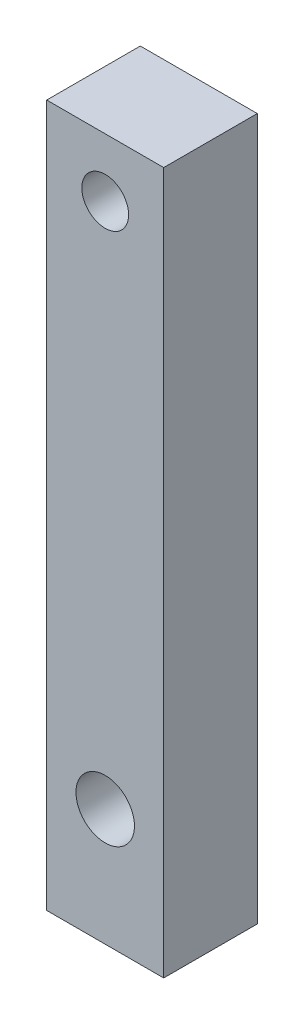
SolidWorks part; units mm, degrees
ref_plane "前视基准面" through (0, 0, 0) normal (0, 0, 1) x (1, 0, 0)
ref_plane "上视基准面" through (0, 0, 0) normal (0, 1, 0) x (1, 0, 0)
ref_plane "右视基准面" through (0, 0, 0) normal (1, 0, 0) x (0, 0, -1)
sketch "草图1" plane through (0, 0, 0) normal (0, 0, 1) x (1, 0, 0)
  line L0 (-3.9706, -31.1949) -> (6.0294, -51.1949) construction
  line L1 (-3.9706, 3.8051) -> (6.0294, 3.8051)
  line L2 (-3.9706, 3.8051) -> (-3.9706, -51.1949)
  line L3 (-3.9706, -51.1949) -> (6.0294, -51.1949)
  line L4 (6.0294, 3.8051) -> (6.0294, -51.1949)
  line L5 (-3.9706, -31.1949) -> (6.0294, -31.1949) construction
  line L6 (1.0294, -31.1949) -> (1.0294, 3.8051) construction
  line L8 (-3.9706, 3.8051) -> (6.0294, 3.8051)
  line L9 (-3.9706, 3.8051) -> (-3.9706, 8.8051)
  line L10 (-3.9706, 8.8051) -> (6.0294, 8.8051)
  line L11 (6.0294, 3.8051) -> (6.0294, 8.8051)
  circle A0 centre (1.0294, -41.1949) radius 2.5
  circle A1 centre (1.0294, 3.8051) radius 2
  point P4 (-3.9706, -31.1949)
  dimension "D4" = 35
  dimension "D1" = 10
  dimension "D2" = 55
  dimension "D3" = 20
  dimension "D5" = 5
extrude "凸台-拉伸1" add sketch "草图1" along normal blind 8 contours A1 L1 L11 L10 L9 | A1 L1 L2 L3 L4 A0
